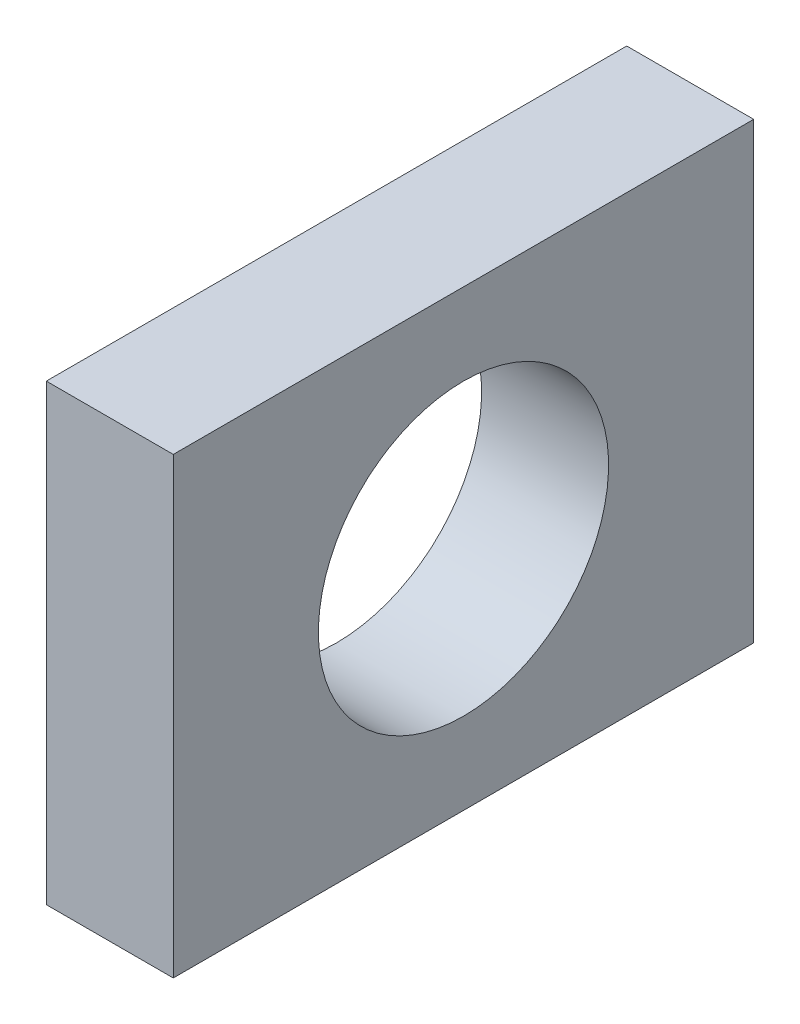
SolidWorks part; units mm, degrees
ref_plane "Front Plane" through (0, 0, 0) normal (0, 0, 1) x (1, 0, 0)
ref_plane "Top Plane" through (0, 0, 0) normal (0, 1, 0) x (1, 0, 0)
ref_plane "Right Plane" through (0, 0, 0) normal (1, 0, 0) x (0, 0, -1)
sketch "Sketch1" plane through (0, 0, 0) normal (0, 0, 1) x (1, 0, 0)
  line L1 (0, 0) -> (1.778, 0)
  line L2 (0, 0) -> (0, -6.35)
  line L3 (0, -6.35) -> (1.778, -6.35)
  line L4 (1.778, 0) -> (1.778, -6.35)
  dimension "D1" = 1.778
  dimension "D2" = 6.35
extrude "Boss-Extrude1" add sketch "Sketch1" along normal blind 8.128
sketch "Sketch2" plane through (0, 0, 0) normal (-1, 0, 0) x (0, 0, 1)
  circle A0 centre (4.064, -3.175) radius 2.032
  dimension "D2" = 4.064
extrude "Cut-Extrude1" cut sketch "Sketch2" against normal through all
